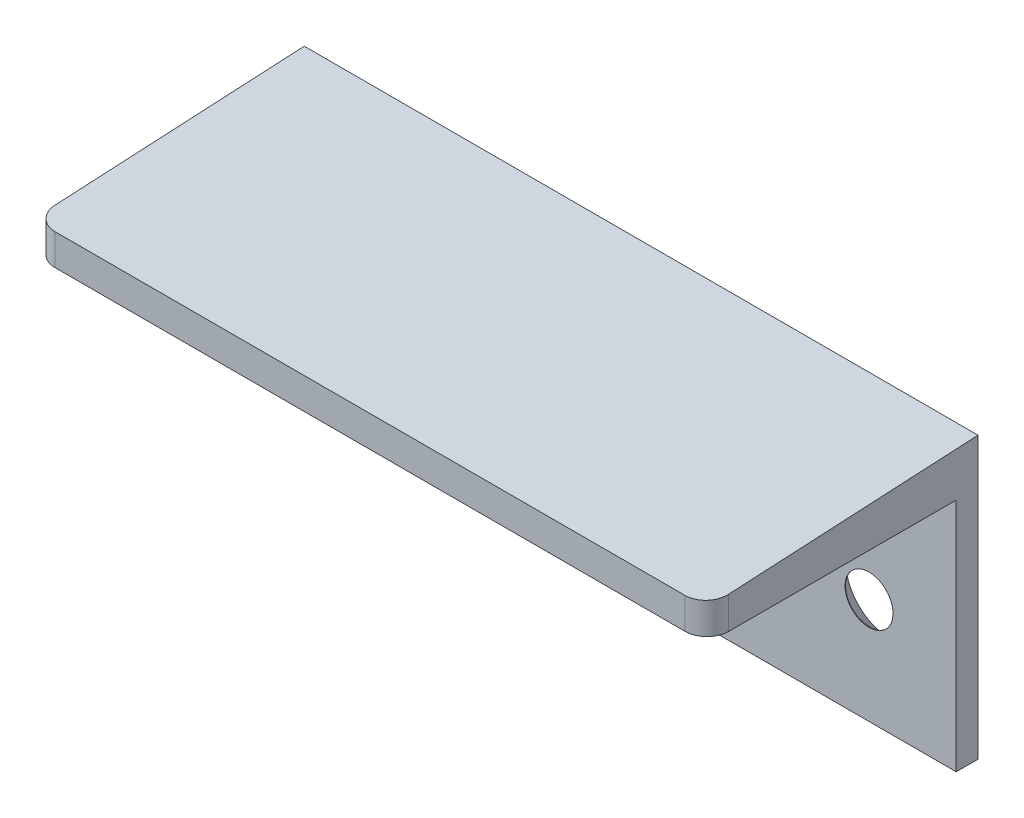
SolidWorks part; units mm, degrees
material "6061 Alloy"
ref_plane "Top Plane" through (0, 0, 0) normal (0, 0, 1) x (1, 0, 0)
ref_plane "Front Plane" through (0, 0, 0) normal (0, 1, 0) x (1, 0, 0)
ref_plane "Right Plane" through (0, 0, 0) normal (1, 0, 0) x (0, 0, -1)
sketch "Sketch1" plane through (0, 0, 0) normal (0, 0, 1) x (1, 0, 0)
  line L1 (-38.65, -16.1) -> (38.65, -16.1)
  line L2 (-38.65, -16.1) -> (-38.65, 16.1)
  line L3 (-38.65, 16.1) -> (38.65, 16.1)
  line L4 (38.65, -16.1) -> (38.65, 16.1)
  line L5 (-38.65, -16.1) -> (38.65, 16.1) construction
  line L6 (-38.65, 16.1) -> (38.65, -16.1) construction
  point P0 (0, 0)
  dimension "D1" = 32.2
  dimension "D2" = 77.3
extrude "Boss-Extrude1" add sketch "Sketch1" along normal blind 2.5
sketch "Sketch3" plane through (0, 0, 2.5) normal (0, 0, 1) x (1, 0, 0)
  line L0 (38.65, -16.1) -> (38.65, 16.1) construction
  line L1 (-38.65, 16.1) -> (38.65, 16.1)
  line L2 (-38.65, 16.1) -> (-38.65, 10.9)
  line L3 (-38.65, 10.9) -> (38.65, 10.9)
  line L4 (38.65, 16.1) -> (38.65, 10.9)
  dimension "D1" = 5.2
extrude "Boss-Extrude2" add sketch "Sketch3" along normal blind 28.599
fillet "Fillet1" radius 2.5 2 edges at (-38.65, 13.5, 31.099) (38.65, 13.5, 31.099)
sketch "Sketch4" plane through (0, 16.1, 0) normal (0, 1, 0) x (1, 0, 0)
  line L0 (38.65, 0) -> (-38.65, 0) construction
  line L1 (-38.65, 0) -> (38.65, 0)
  line L2 (-38.65, 0) -> (-38.65, -37.3428)
  line L3 (-38.65, -37.3428) -> (38.65, -37.3428)
  line L4 (38.65, 0) -> (38.65, -37.3428)
  line L5 (-38.65, -28.599) -> (-38.65, 0) construction
revolve "Cut-Revolve2" cut sketch "Sketch4" angle 3 about L1
hole_wizard "CSK for M5 Flat Head Machine Screw1" positions "Sketch5" profile "Sketch6" countersink size "M5" standard "ANSI Metric"
sketch "Sketch5" plane through (0, 0, 0) normal (0, 0, -1) x (-1, 0, 0)
  line L0 (-38.65, -16.1) -> (-38.65, 16.1) construction
  line L1 (38.65, 16.1) -> (38.65, -16.1) construction
  line L2 (-38.65, 16.1) -> (38.65, 16.1) construction
  point P0 (-28.65, -4)
  point P2 (28.65, -4)
  dimension "D1" = 10
  dimension "D2" = 10
  dimension "D3" = 20.1
  dimension "D4" = 20.1
sketch "Sketch6" plane through (28.65, -4, 0) normal (1, 0, 0) x (0, 1, 0)
  line L0 (0, 0) -> (0, 14.0524)
  line L1 (0, 14.0524) -> (2.75, 12.4)
  line L2 (2.75, 12.4) -> (2.75, 2.45)
  line L3 (2.75, 2.45) -> (5.2, 0)
  line L5 (5.2, 0) -> (0, 0)
  line L6 (-2.75, 2.45) -> (-5.2, 0) construction
  line L10 (0, 14.0524) -> (-2.75, 12.4) construction
  line L11 (0, -6.35) -> (0, 107.95) construction
  dimension "Hole Dia." = 5.5
  dimension "Hole Depth" = 12.4
  dimension "Near C'Sink Dia." = 10.4
  dimension "Near C'Sink Angle" = 90
  dimension "Drill Angle" = 118
